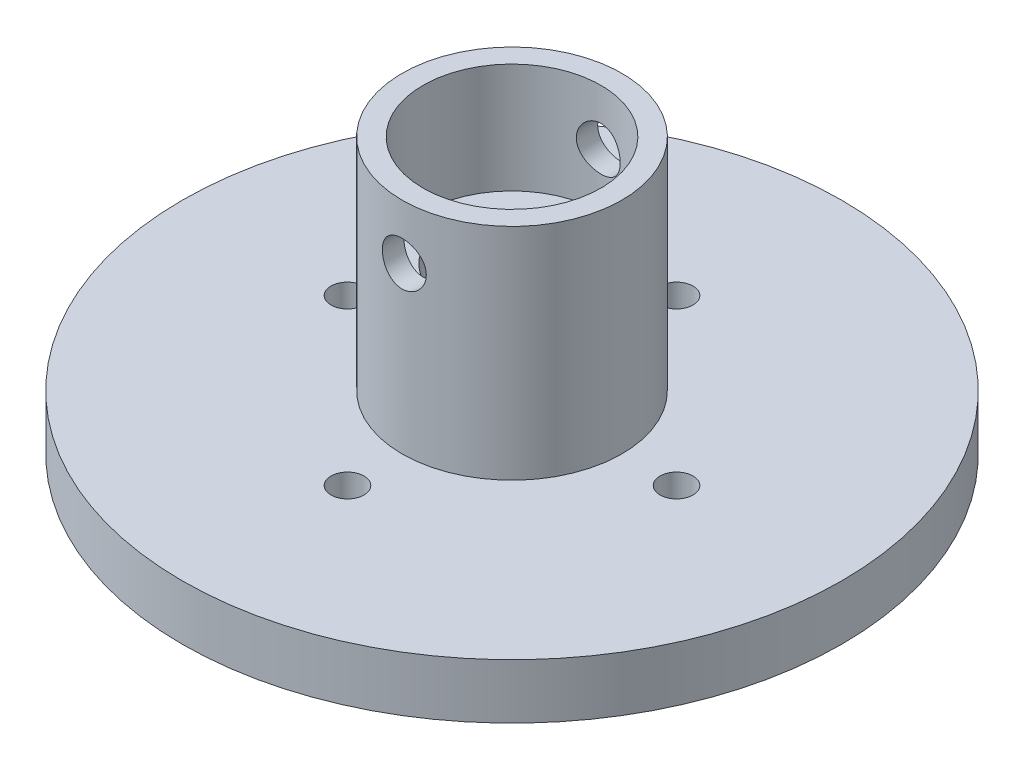
SolidWorks part; units mm, degrees
ref_plane "Front Plane" through (0, 0, 0) normal (0, 0, 1) x (1, 0, 0)
ref_plane "Top Plane" through (0, 0, 0) normal (0, 1, 0) x (1, 0, 0)
ref_plane "Right Plane" through (0, 0, 0) normal (1, 0, 0) x (0, 0, -1)
sketch "Sketch1" plane through (0, 0, 0) normal (0, 1, 0) x (1, 0, 0)
  circle A0 centre (0, 0) radius 30
extrude "Boss-Extrude1" add sketch "Sketch1" along normal blind 5
sketch "Sketch2" plane through (0, 5, 0) normal (0, 1, 0) x (1, 0, 0)
  circle A0 centre (0, 0) radius 10
extrude "Boss-Extrude2" add sketch "Sketch2" along normal blind 90
sketch "Sketch4" plane through (0, 95, 0) normal (0, 1, 0) x (1, 0, 0)
  circle A0 centre (0, 0) radius 6
extrude "Cut-Extrude2" cut sketch "Sketch4" against normal blind 200
sketch "Sketch5" plane through (0, 5, 0) normal (0, 1, 0) x (1, 0, 0)
  circle A0 centre (0, 0) radius 14.9698
  circle A1 centre (0, 14.9698) radius 1.5
  circle A2 centre (14.9698, 0) radius 1.5
  circle A3 centre (0, -14.9698) radius 1.5
  circle A4 centre (-14.9698, 0) radius 1.5
extrude "Cut-Extrude3" cut sketch "Sketch5" against normal blind 10 contours A1 | A2 | A3 | A4
sketch "Sketch6" plane through (0, 95, 0) normal (0, 1, 0) x (1, 0, 0)
  circle A0 centre (0, 0) radius 8
extrude "Cut-Extrude4" cut sketch "Sketch6" against normal blind 10
sketch "Sketch7" plane through (0, 95, 0) normal (0, 1, 0) x (1, 0, 0)
  line L0 (0, 0) -> (0, 10)
  circle A0 centre (0, 0) radius 10 construction
ref_plane "Plane1" through (0, 95, -10) normal (0, 0, -1) x (-1, 0, 0)
sketch "Sketch8" plane through (0, 95, -10) normal (0, 0, -1) x (-1, 0, 0)
  line L0 (0, 0) -> (0, -5)
  line L1 (8, 0) -> (-8, 0) construction
  circle A0 centre (0, -5) radius 2
extrude "Cut-Extrude5" cut sketch "Sketch8" against normal blind 20 contours A0
sketch "Sketch10" plane through (0, 95, 0) normal (0, 1, 0) x (1, 0, 0)
  circle A0 centre (0, 0) radius 10
extrude "Cut-Extrude6" cut sketch "Sketch10" against normal blind 70
sketch "Sketch12" plane through (0, 25, 0) normal (0, 1, 0) x (1, 0, 0)
  circle A0 centre (0, 0) radius 8.1
extrude "Cut-Extrude7" cut sketch "Sketch12" against normal blind 10
sketch "Sketch13" plane through (0, 95, -10) normal (0, 0, -1) x (-1, 0, 0)
  line L0 (0, -70) -> (0, -75)
  line L1 (8.1, -70) -> (-8.1, -70) construction
  circle A0 centre (0, -75) radius 2
extrude "Cut-Extrude8" cut sketch "Sketch13" against normal blind 20 contours A0
